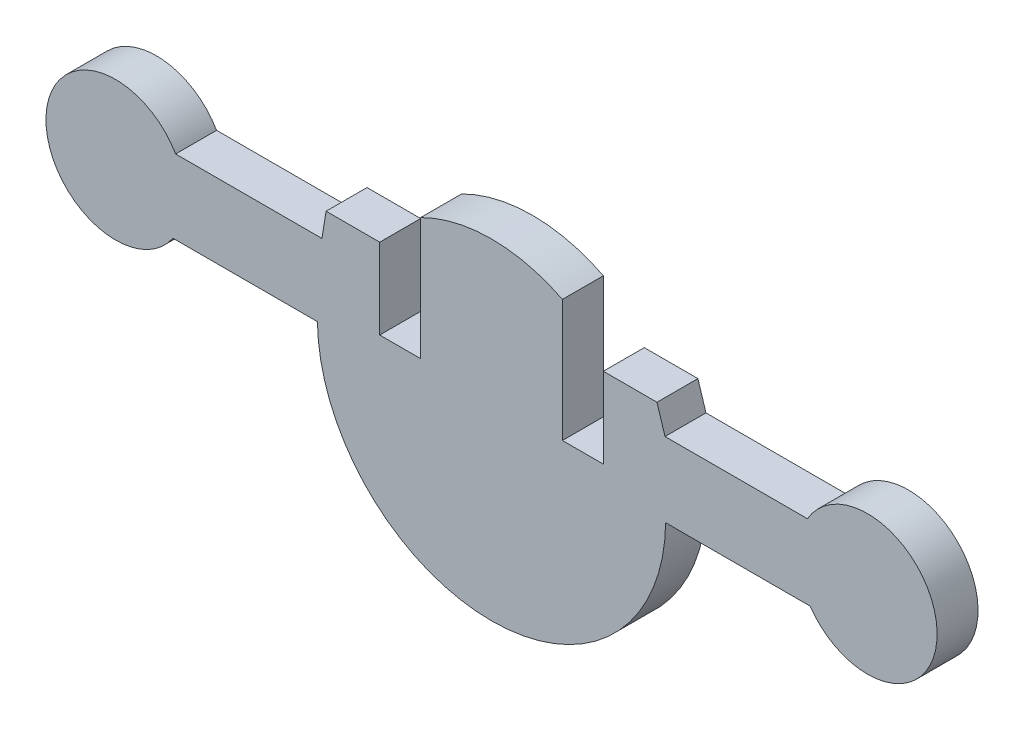
SolidWorks part; units mm, degrees
ref_plane "Front" through (0, 0, 0) normal (0, 0, 1) x (1, 0, 0)
ref_plane "Top" through (0, 0, 0) normal (0, 1, 0) x (1, 0, 0)
ref_plane "Right" through (0, 0, 0) normal (1, 0, 0) x (0, 0, -1)
sketch "Sketch1" plane through (0, 0, 0) normal (0, 0, 1) x (1, 0, 0)
  line L0 (380.1629, 81.0233) -> (390.599, 81.0233)
  line L1 (380.2078, 75.5756) -> (390.7951, 75.5756)
  line L2 (355.0186, 81.0233) -> (355.3214, 82.9054)
  line L4 (354.687, 75.5756) -> (344.0997, 75.5756)
  line L6 (355.0186, 81.0233) -> (344.2958, 81.0233)
  line L7 (372.6424, 85.9661) -> (372.6424, 77.01)
  line L8 (372.6424, 77.01) -> (375.6424, 77.01)
  line L9 (375.6424, 77.01) -> (375.6424, 82.9054)
  line L10 (362.2524, 85.9661) -> (362.2524, 77.01)
  line L11 (362.2524, 77.01) -> (359.2524, 77.01)
  line L12 (359.2524, 77.01) -> (359.2524, 82.9054)
  line L19 (359.2524, 82.9054) -> (355.3214, 82.9054)
  line L20 (375.6424, 82.9054) -> (379.5734, 82.9054)
  line L21 (380.1629, 81.0233) -> (379.5734, 82.9054)
  arc A0 (390.599, 81.0233) -> (390.7951, 75.5756) centre (395.0048, 78.4545) cw
  arc A1 (344.2958, 81.0233) -> (344.0997, 75.5756) centre (339.89, 78.4545) ccw
  arc A2 (362.2524, 85.9661) -> (372.6424, 85.9661) centre (367.4474, 75.7242) cw
  arc A4 (354.687, 75.5756) -> (380.2078, 75.5756) centre (367.4474, 75.7242) ccw
  dimension "D1" = 3
  dimension "D2" = 3
  dimension "D3" = 10.39
extrude "Base-Extrude" add sketch "Sketch1" along normal blind 3
